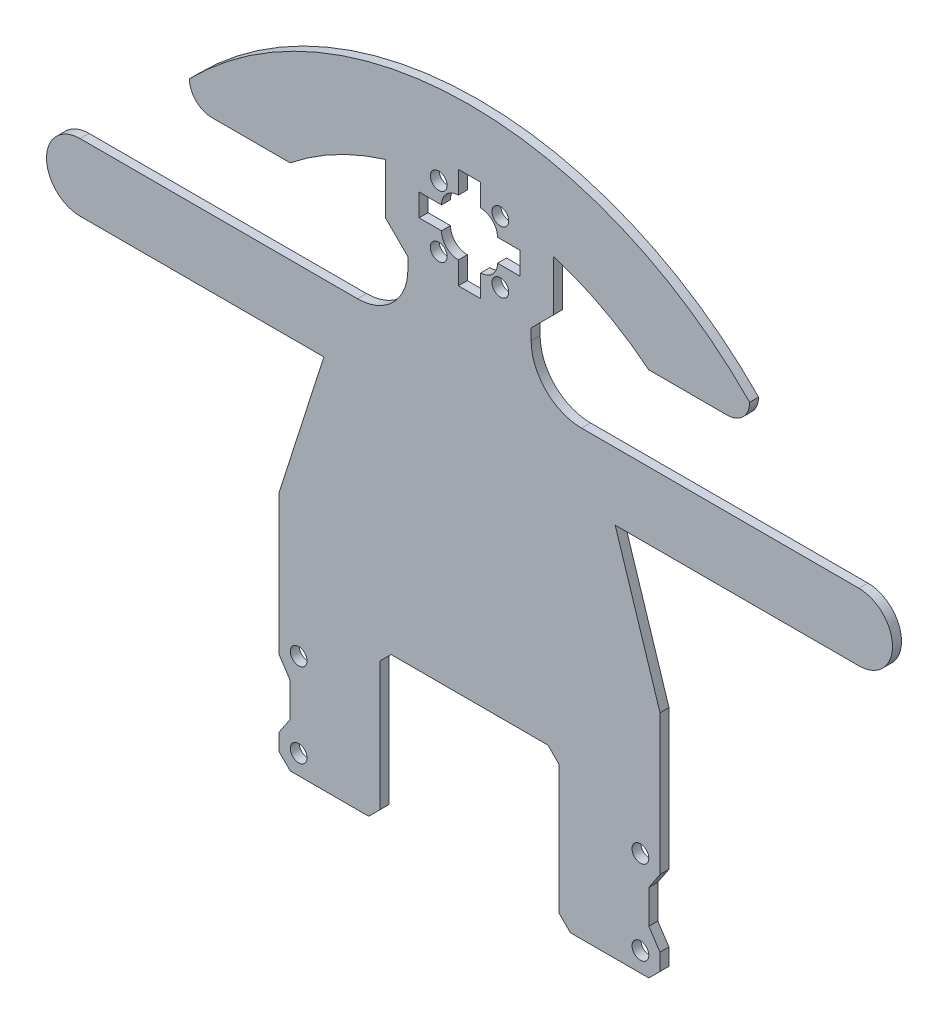
SolidWorks part; units mm, degrees
ref_plane "Plano frontal" through (0, 0, 0) normal (0, 0, 1) x (1, 0, 0)
ref_plane "Plano superior" through (0, 0, 0) normal (0, 1, 0) x (1, 0, 0)
ref_plane "Plano direito" through (0, 0, 0) normal (1, 0, 0) x (0, 0, -1)
sketch "Esboço1" plane through (0, 0, 0) normal (0, 0, 1) x (1, 0, 0)
  line L0 (14, 0) -> (-14, 0)
  line L29 (-16, -2) -> (-14, 0)
  line L30 (-16, -2) -> (-16, -25)
  line L33 (-18, -27) -> (-16, -25)
  line L34 (-18, -27) -> (-32, -27)
  line L37 (-34, -25) -> (-32, -27)
  line L38 (-34, -25) -> (-34, -22)
  line L41 (-34, -22) -> (-32, -19)
  line L42 (-32, -19) -> (-32, -13)
  line L45 (-32, -13) -> (-34, -10)
  line L46 (-34, -10) -> (-34, 15)
  line L49 (-34, 15) -> (-26, 40)
  line L50 (-26, 40) -> (-69.5, 40)
  line L51 (-69.5, 52) -> (-20, 52)
  line L52 (-11, 61) -> (-11, 63)
  line L55 (-11, 63) -> (-15, 67)
  line L56 (-15, 67) -> (-15, 76)
  line L59 (-32, 67) -> (-46, 67)
  line L65 (-15.1074, 76) -> (-15, 76)
  line L66 (15.1074, 76) -> (15, 76)
  line L68 (32, 67) -> (46, 67)
  line L70 (15, 67) -> (15, 76)
  line L71 (11, 63) -> (15, 67)
  line L72 (11, 61) -> (11, 63)
  line L73 (69.5, 52) -> (20, 52)
  line L74 (26, 40) -> (69.5, 40)
  line L75 (34, 15) -> (26, 40)
  line L76 (34, -10) -> (34, 15)
  line L77 (32, -13) -> (34, -10)
  line L78 (32, -19) -> (32, -13)
  line L79 (34, -22) -> (32, -19)
  line L80 (34, -25) -> (34, -22)
  line L81 (34, -25) -> (32, -27)
  line L82 (18, -27) -> (32, -27)
  line L83 (18, -27) -> (16, -25)
  line L84 (16, -2) -> (16, -25)
  line L85 (16, -2) -> (14, 0)
  arc A0 (-69.5, 40) -> (-69.5, 52) centre (-69.5, 46) cw
  arc A1 (-20, 52) -> (-11, 61) centre (-20, 61) ccw
  arc A3 (46, 67) -> (50, 71) centre (46, 71) ccw
  arc A4 (20, 52) -> (11, 61) centre (20, 61) cw
  arc A5 (69.5, 40) -> (69.5, 52) centre (69.5, 46) ccw
  arc A6 (50, 71) -> (-50, 71) centre (0, 21.9762) ccw
  arc A7 (-46, 67) -> (-50, 71) centre (-46, 71) cw
  arc A8 (-32, 67) -> (-15.1074, 76) centre (0, 27.2907) cw
  arc A9 (15.1074, 76) -> (32, 67) centre (0, 27.2907) cw
extrude "Ressalto-extrusão1" add sketch "Esboço1" along normal blind 1.6
sketch "Esboço2" plane through (0, 0, 0) normal (0, 0, -1) x (-1, 0, 0)
  line L0 (-5, 70) -> (-9, 70)
  line L1 (-2, 81) -> (2, 81)
  line L2 (-2, 81) -> (-2, 77)
  line L3 (-2, 63) -> (2, 63)
  line L4 (2, 81) -> (2, 77)
  line L5 (2, 67) -> (2, 63)
  line L6 (-15, 67) -> (-15, 76) construction
  line L7 (-5, 74) -> (-9, 74)
  line L8 (9, 74) -> (5, 74)
  line L9 (9, 74) -> (9, 70)
  line L10 (9, 70) -> (5, 70)
  line L11 (-9, 74) -> (-9, 70)
  line L12 (-2, 67) -> (-2, 63)
  line L13 (15, 76) -> (15, 67) construction
  arc A0 (5, 74) -> (2, 77) centre (2, 74) ccw
  arc A1 (2, 67) -> (5, 70) centre (2, 70) ccw
  arc A2 (-5, 70) -> (-2, 67) centre (-2, 70) ccw
  arc A3 (-2, 77) -> (-5, 74) centre (-2, 74) ccw
  circle A4 centre (5.5, 66.5) radius 1.5
  circle A5 centre (-5.5, 66.5) radius 1.5
  circle A6 centre (-5.5, 77.5) radius 1.5
  circle A7 centre (5.5, 77.5) radius 1.5
  dimension "D1" = 3
  dimension "D8" = 3
  dimension "D11" = 3
  dimension "D14" = 3
  dimension "D17" = 3
  dimension "D20" = 3
  dimension "D21" = 3.5
  dimension "D22" = 3.5
  dimension "D2" = 4
  dimension "D3" = 18
  dimension "D4" = 13
  dimension "D5" = 18
  dimension "D6" = 4
  dimension "D7" = 7
  dimension "D9" = 3
  dimension "D10" = 3
  dimension "D12" = 3.5
  dimension "D13" = 3.5
  dimension "D15" = 3.5
  dimension "D16" = 3.5
  dimension "D18" = 3.5
  dimension "D19" = 3.5
  dimension "D23" = 6
extrude "Corte-extrusão2" cut sketch "Esboço2" against normal blind 2
sketch "Esboço3" plane through (0, 0, 1.6) normal (0, 0, 1) x (1, 0, 0)
  line L0 (-32, -27) -> (-18, -27) construction
  line L1 (-34, -22) -> (-34, -25) construction
  line L3 (18, -27) -> (32, -27) construction
  line L4 (34, -25) -> (34, -22) construction
  circle A0 centre (-30.5, -23.5) radius 1.5
  circle A1 centre (30.5, -23.5) radius 1.5
  dimension "D1" = 3
  dimension "D2" = 3.5
  dimension "D3" = 3.5
  dimension "D4" = 3
  dimension "D5" = 3.5
  dimension "D6" = 3.5
extrude "Corte-extrusão3" cut sketch "Esboço3" against normal blind 10
sketch "Esboço4" plane through (0, 0, 1.6) normal (0, 0, 1) x (1, 0, 0)
  line L0 (-34, 15) -> (-34, -10) construction
  line L1 (-32, -27) -> (-18, -27) construction
  line L2 (34, -10) -> (34, 15) construction
  line L3 (18, -27) -> (32, -27) construction
  circle A0 centre (-30.5, -8.5) radius 1.5
  circle A1 centre (30.5, -8.5) radius 1.5
  dimension "D1" = 3.5
  dimension "D2" = 3
  dimension "D3" = 18.5
  dimension "D4" = 3
  dimension "D5" = 3.5
  dimension "D6" = 18.5
extrude "Corte-extrusão4" cut sketch "Esboço4" against normal blind 10
